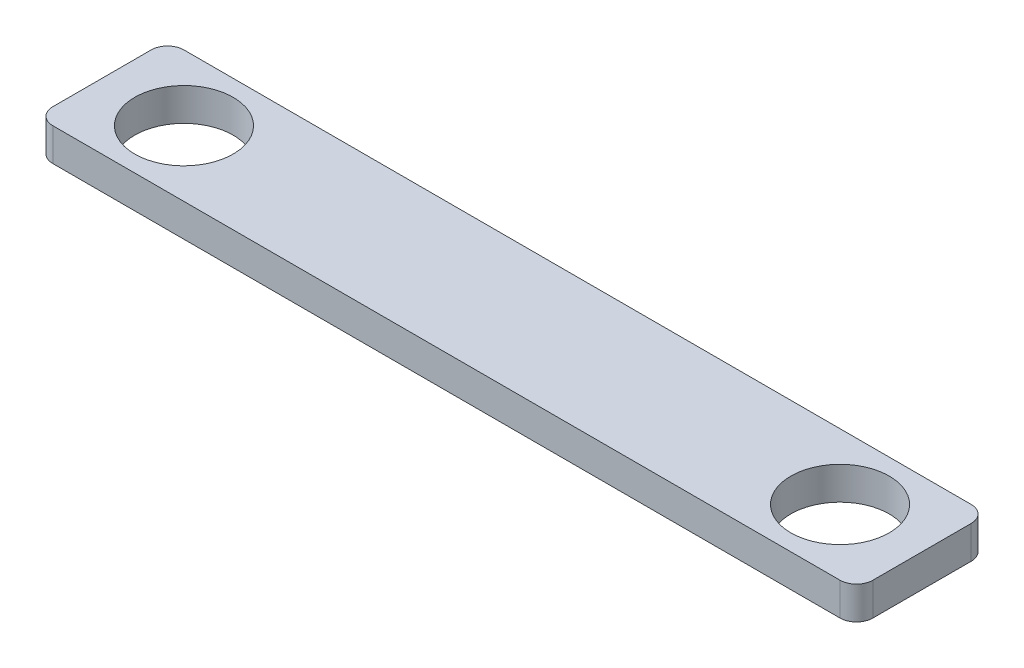
SolidWorks part; units mm, degrees
ref_plane "Front" through (0, 0, 0) normal (0, 0, 1) x (1, 0, 0)
ref_plane "Top" through (0, 0, 0) normal (0, 1, 0) x (1, 0, 0)
ref_plane "Right" through (0, 0, 0) normal (1, 0, 0) x (0, 0, -1)
sketch "Sketch1" plane through (0, 0, 0) normal (0, 1, 0) x (1, 0, 0)
  line L0 (-63.5, 0) -> (63.5, 0) construction
  line L1 (60.96, -10.16) -> (-60.96, -10.16)
  line L2 (63.5, -7.62) -> (63.5, 7.62)
  line L3 (60.96, 10.16) -> (-60.96, 10.16)
  line L4 (-63.5, -7.62) -> (-63.5, 7.62)
  line L5 (63.5, -10.16) -> (-63.5, 10.16) construction
  line L6 (63.5, 10.16) -> (-63.5, -10.16) construction
  circle A0 centre (-50.8, 0) radius 7.62
  circle A1 centre (50.8, 0) radius 7.62
  arc A2 (60.96, -10.16) -> (63.5, -7.62) centre (60.96, -7.62) ccw
  arc A3 (63.5, 7.62) -> (60.96, 10.16) centre (60.96, 7.62) ccw
  arc A4 (-60.96, -10.16) -> (-63.5, -7.62) centre (-60.96, -7.62) cw
  arc A5 (-63.5, 7.62) -> (-60.96, 10.16) centre (-60.96, 7.62) cw
  point P0 (0, 0)
  dimension "D3" = 15.24
  dimension "D4" = 15.24
  dimension "D7" = 2.54
  dimension "D1" = 127
  dimension "D2" = 20.32
  dimension "D5" = 50.8
  dimension "D6" = 50.8
extrude "Boss-Extrude1" add sketch "Sketch1" along normal blind 5.08
